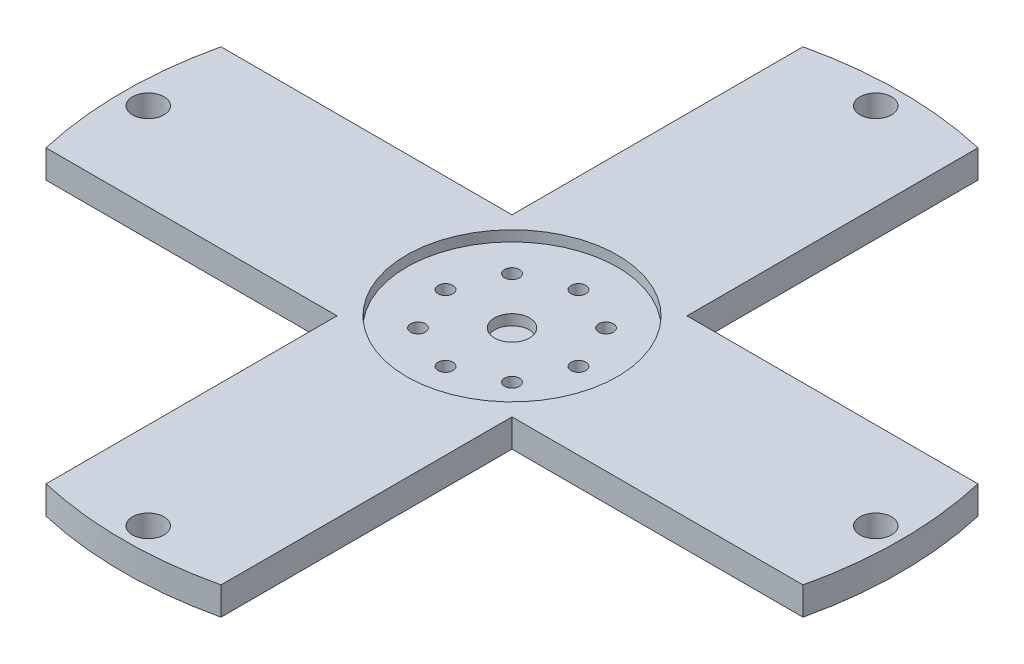
SolidWorks part; units mm, degrees
ref_plane "前视基准面" through (0, 0, 0) normal (0, 0, 1) x (1, 0, 0)
ref_plane "上视基准面" through (0, 0, 0) normal (0, 1, 0) x (1, 0, 0)
ref_plane "右视基准面" through (0, 0, 0) normal (1, 0, 0) x (0, 0, -1)
sketch "草图1" plane through (0, 0, 0) normal (0, 1, 0) x (1, 0, 0)
  line L0 (-25, 108.148) -> (-25, 25)
  line L1 (25, 108.148) -> (25, 25)
  line L3 (-108.148, 25) -> (-25, 25)
  line L4 (-108.148, -25) -> (-25, -25)
  line L5 (-25, -25) -> (-25, -108.148)
  line L6 (25, -25) -> (25, -108.148)
  line L7 (25, -25) -> (108.148, -25)
  line L8 (25, 25) -> (108.148, 25)
  circle A1 centre (0, 19) radius 2.1
  circle A2 centre (13.435, 13.435) radius 2.1
  circle A3 centre (19, 0) radius 2.1
  circle A4 centre (13.435, -13.435) radius 2.1
  circle A5 centre (0, -19) radius 2.1
  circle A6 centre (-13.435, -13.435) radius 2.1
  circle A7 centre (-19, 0) radius 2.1
  circle A8 centre (-13.435, 13.435) radius 2.1
  circle A9 centre (0, 103.945) radius 4.5
  arc A12 (-108.148, 25) -> (-108.148, -25) centre (0, 0) ccw
  circle A13 centre (103.945, 0) radius 4.5
  circle A14 centre (0, -103.945) radius 4.5
  circle A15 centre (-103.945, 0) radius 4.5
  arc A16 (25, 108.148) -> (-25, 108.148) centre (0, 0) ccw
  arc A17 (108.148, -25) -> (108.148, 25) centre (0, 0) ccw
  arc A18 (-25, -108.148) -> (25, -108.148) centre (0, 0) ccw
  point P25 (0, 0)
  point P26 (0, 0)
  point P41 (0, 0)
  dimension "D11" = 4
  dimension "D6" = 8
extrude "凸台-拉伸1" add sketch "草图1" along normal blind 8
sketch "草图2" plane through (0, 8, 0) normal (0, 1, 0) x (1, 0, 0)
  circle A0 centre (0, 0) radius 30.1208
extrude "切除-拉伸1" cut sketch "草图2" against normal blind 3
sketch "草图3" plane through (0, 5, 0) normal (0, 1, 0) x (1, 0, 0)
  circle A0 centre (0, 0) radius 5
  dimension "D1" = 10
extrude "切除-拉伸2" cut sketch "草图3" against normal blind 3
